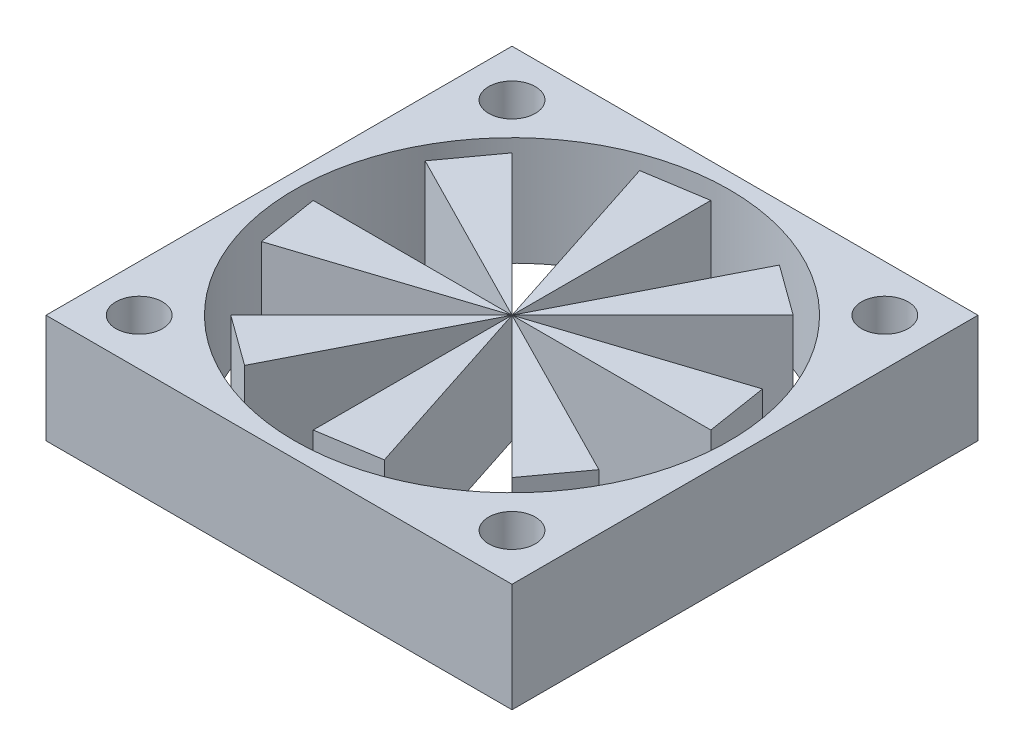
SolidWorks part; units mm, degrees
ref_plane "前视基准面" through (0, 0, 0) normal (0, 0, 1) x (1, 0, 0)
ref_plane "上视基准面" through (0, 0, 0) normal (0, 1, 0) x (1, 0, 0)
ref_plane "右视基准面" through (0, 0, 0) normal (1, 0, 0) x (0, 0, -1)
sketch "草图1" plane through (0, 0, 0) normal (0, 1, 0) x (1, 0, 0)
  line L0 (1.16, 15.76) -> (1.16, -14.24) construction
  line L1 (-13.84, 15.76) -> (16.16, 15.76)
  line L2 (-13.84, 15.76) -> (-13.84, -14.24)
  line L3 (-13.84, -14.24) -> (16.16, -14.24)
  line L4 (16.16, 15.76) -> (16.16, -14.24)
  line L5 (-13.84, 0.76) -> (16.16, 0.76) construction
  circle A0 centre (-10.84, 12.76) radius 1.5
  circle A1 centre (-10.84, -11.24) radius 1.5
  circle A2 centre (13.16, -11.24) radius 1.5
  circle A3 centre (13.16, 12.76) radius 1.5
  circle A4 centre (1.16, 0.76) radius 14
  point P10 (1.16, 0.76)
  dimension "D6" = 3
  dimension "D7" = 28
  dimension "D1" = 30
  dimension "D2" = 30
  dimension "D3" = 12
  dimension "D4" = 12
  dimension "D5" = 4
extrude "凸台-拉伸1" add sketch "草图1" along normal blind 7
sketch "草图2" plane through (0, 0, 0) normal (0, -1, 0) x (1, 0, 0)
  line L0 (16.16, -15.76) -> (-13.84, -15.76) construction
  line L1 (1.16, -15.76) -> (1.16, 14.24) construction
  line L2 (-13.84, 14.24) -> (16.16, 14.24) construction
  line L3 (16.16, -0.76) -> (-13.84, -0.76) construction
  line L4 (16.16, 14.24) -> (16.16, -15.76) construction
  line L5 (-13.84, -15.76) -> (-13.84, 14.24) construction
  line L6 (1.16, -0.76) -> (1.16, -13.56)
  line L7 (1.16, -13.56) -> (-2.7954, -12.9335)
  line L8 (-2.7954, -12.9335) -> (1.16, -0.76)
  line L9 (-7.891, -9.811) -> (-10.2449, -6.5711)
  line L10 (-10.2449, -6.5711) -> (1.16, -0.76)
  line L11 (1.16, -0.76) -> (-7.891, -9.811)
  line L12 (-11.64, -0.76) -> (-11.0135, 3.1954)
  line L13 (-11.0135, 3.1954) -> (1.16, -0.76)
  line L14 (1.16, -0.76) -> (-11.64, -0.76)
  line L15 (-7.891, 8.291) -> (-4.6511, 10.6449)
  line L16 (-4.6511, 10.6449) -> (1.16, -0.76)
  line L17 (1.16, -0.76) -> (-7.891, 8.291)
  line L18 (1.16, 12.04) -> (5.1154, 11.4135)
  line L19 (5.1154, 11.4135) -> (1.16, -0.76)
  line L20 (1.16, -0.76) -> (1.16, 12.04)
  line L21 (10.211, 8.291) -> (12.5649, 5.0511)
  line L22 (12.5649, 5.0511) -> (1.16, -0.76)
  line L23 (1.16, -0.76) -> (10.211, 8.291)
  line L24 (13.96, -0.76) -> (13.3335, -4.7154)
  line L25 (13.3335, -4.7154) -> (1.16, -0.76)
  line L26 (1.16, -0.76) -> (13.96, -0.76)
  line L27 (10.211, -9.811) -> (6.9711, -12.1649)
  line L28 (6.9711, -12.1649) -> (1.16, -0.76)
  line L29 (1.16, -0.76) -> (10.211, -9.811)
  dimension "D1" = 12.8
  dimension "D2" = 12.8
  dimension "D3" = 18
  dimension "D4" = 8
extrude "凸台-拉伸2" add sketch "草图2" against normal blind 7 separate body contours L29 L28 L27 | L8 L7 L6 | L11 L10 L9 | L14 L13 L12 | L17 L16 L15 | L20 L19 L18 | L23 L22 L21 | L26 L25 L24
